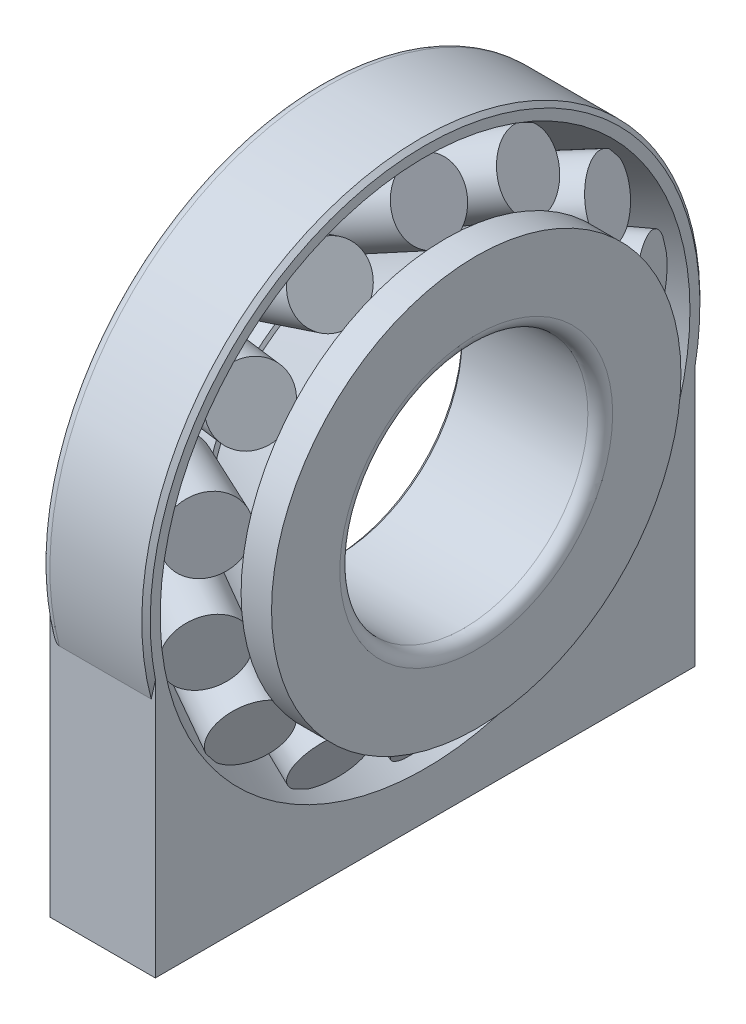
SolidWorks part; units mm, degrees
revolve "OuterRace" add sketch "OutRacSke" angle 360 about L5
sketch "OutRacSke" plane through (0, 0, 0) normal (0, 0, 1) x (1, 0, 0)
  line L0 (-8.25, 42.7146) -> (-25.25, 33.492)
  line L1 (-25.25, 33.492) -> (-25.25, 43.5)
  line L2 (-23.75, 45) -> (-8.93, 45)
  line L3 (-8.93, 45) -> (-8.25, 44.32)
  line L4 (-8.25, 44.32) -> (-8.25, 42.7146)
  line L5 (-42.5, 0) -> (42.5, 0) construction
  arc A0 (-25.25, 43.5) -> (-23.75, 45) centre (-23.75, 43.5) cw
  dimension "cup_radius" = 1.5
  dimension "OD" = 90
  dimension "cup_width" = 17
  dimension "Tangle" = 28.48
  dimension "offset" = 25.25
  dimension "chamfer" = 0.68
  dimension "D8" = 45
  dimension "cup_SID" = 66.984
ref_plane "Plane1" through (0, 0, 0) normal (0, 0, 1) x (1, 0, 0)
ref_plane "Plane2" through (0, 0, 0) normal (0, 1, 0) x (1, 0, 0)
ref_plane "Plane3" through (0, 0, 0) normal (1, 0, 0) x (0, 0, -1)
sketch "Clipboard" plane through (0, 0, 0) normal (0, 0, 1) x (1, 0, 0)
  line L0 (0, 0) -> (10, 0) construction
  line L1 (0, 0) -> (64.9943, -16.2049)
  line L2 (0, 0) -> (38.8118, 9.6769)
  line L3 (0, 0) -> (87.3266, -21.773)
  line L4 (0, 0) -> (-15.2977, -0.267)
  line L5 (0, 0) -> (-11.25, 25.25)
  dimension "Bore" = 40
  dimension "Count" = 14
  dimension "Show_count" = 14
  dimension "Max_count" = 14
  dimension "Min_count" = 1
  dimension "Race_OD" = 90
  dimension "Race_ID" = 66.984
  dimension "cyl_len" = 15.3
  dimension "Roller_diameter" = 11.25
  dimension "OA_width" = 25.25
sketch "RolDetSke" plane through (0, 0, 0) normal (0, 0, 1) x (1, 0, 0)
  line L0 (-21.0677, 29.533) -> (-23.75, 34.4773)
  line L1 (-21.0677, 29.533) -> (-7.6193, 36.8288)
  line L2 (-10.3016, 41.7731) -> (-7.6193, 36.8288)
  line L4 (-33.4195, 22.8321) -> (13.1575, 48.1003) construction
  line L5 (-10.3016, 41.7731) -> (-23.75, 34.4773)
  line L9 (-8.25, 42.7146) -> (-25.25, 33.492) construction
  dimension "cyl_len" = 15.3
  dimension "Roller_diameter" = 11.25
  dimension "dy" = 34.4773
  dimension "D2" = 23.75
revolve "RollerDetailed" add sketch "RolDetSke" angle 360 about L4
sketch "RolSimSke" plane through (0, 0, 0) normal (0, 0, 1) x (1, 0, 0)
  line L0 (0, 0) -> (-32, 0) construction
  line L1 (-23.75, 34.4773) -> (-10.3016, 41.7731)
  line L2 (-23.75, 34.4773) -> (-18.3854, 24.5887)
  line L3 (-18.3854, 24.5887) -> (-4.937, 31.8846)
  line L4 (-10.3016, 41.7731) -> (-4.937, 31.8846)
  dimension "Tangle" = 28.48
  dimension "Roller_diameter" = 11.25
  dimension "dy" = 34.4773
  dimension "dx" = 23.75
revolve "RollersSimplified" [suppressed] add sketch "RolSimSke" angle 360 about L0
ref_axis "Axis1" through (-50, 0, 0) along (1, 0, 0)
pattern_circular "RollersDetailed" count 14 every 25.714 about axis through (-50, 0, 0) along (1, 0, 0) of "RollerDetailed", "OuterRace"
sketch "InsRacSke" plane through (0, 0, 0) normal (0, 0, 1) x (1, 0, 0)
  line L0 (-18.6638, 25.1512) -> (-23, 25.1512)
  line L1 (-25.25, 43.5) -> (-25.25, -43.5) construction
  line L2 (-23, 25.1512) -> (-23, 20.68)
  line L3 (-23, 20.68) -> (-22.32, 20)
  line L4 (-22.32, 20) -> (-2, 20)
  line L5 (0, 22) -> (0, 33.0096)
  line L6 (0, 33.0096) -> (-4.9101, 33.0096)
  line L7 (-4.9101, 33.0096) -> (-4.9101, 31.8846)
  line L8 (-4.9101, 31.8846) -> (-18.3586, 24.5887)
  line L9 (-18.3586, 24.5887) -> (-18.6638, 25.1512)
  line L10 (-42.5, 0) -> (42.5, 0) construction
  arc A0 (-2, 20) -> (0, 22) centre (-2, 22) ccw
  dimension "Tangle" = 28.48
  dimension "chamfer" = 0.68
  dimension "Bore" = 40
  dimension "cyl_len" = 15.3
  dimension "dy" = 24.5887
  dimension "dx" = 18.3586
  dimension "D11" = 45
  dimension "D2" = 25.25
revolve "InnerRace" add sketch "InsRacSke" angle 360 about L10
sketch "CagSpiSke" plane through (0, 0, 0) normal (0, 0, 1) x (1, 0, 0)
  line L3 (-6.9468, 37.0221) -> (-21.0677, 29.3615)
  line L4 (-21.3693, 28.3446) -> (-20.654, 27.0261)
  line L6 (-42.5, 0) -> (42.5, 0) construction
  arc A1 (-21.0677, 29.3615) -> (-21.3693, 28.3446) centre (-20.7101, 28.7022) ccw
  dimension "Tangle" = 28.48
  dimension "radius" = 0.75
  dimension "dx" = 21.0677
  dimension "dy" = 29.3615
  dimension "offset" = 2.25
revolve "CageSpine" [suppressed] add sketch "CagSpiSke" angle 0.001 about L6
sketch "Esquisse2" plane through (-25.25, 0, 0) normal (-1, 0, 0) x (0, 0, 1)
  line L0 (-43.5, 0) -> (-43.5, -50.1949)
  line L1 (-43.5, -50.1949) -> (43.5, -50.1949)
  line L2 (43.5, -50.1949) -> (43.4753, -1.4655)
  circle A0 centre (0, 0) radius 43.5 construction
  arc A1 (-43.5, 0) -> (43.4753, -1.4655) centre (0, 0) ccw
extrude "Boss.-Extru.1" add sketch "Esquisse2" against normal blind 17
equation "\"OD@OutRacSke\" = \"Race_OD@Clipboard\""
equation "\"cup_SID@OutRacSke\" = \"Race_ID@Clipboard\""
equation "\"chamfer@OutRacSke\" = \"cup_width@OutRacSke\" / 25"
equation "\"offset@OutRacSke\" = \"OA_width@Clipboard\""
equation "\"D2@RolDetSke\" = \"offset@OutRacSke\" - \"cup_radius@OutRacSke\""
equation "\"dy@RolDetSke\" =  ( ( \"Race_ID@Clipboard\" / 2 ) + ( \"cup_radius@OutRacSke\" ) * tan(\"Tangle@OutRacSke\" * 3.141592654/180) ) * 1.005"
equation "\"cyl_len@RolDetSke\" = \"cyl_len@Clipboard\""
equation "\"Roller_diameter@RolDetSke\" = \"Roller_diameter@Clipboard\""
equation "\"dx@RolSimSke\" = \"offset@OutRacSke\" - \"cup_radius@OutRacSke\""
equation "\"dy@RolSimSke\" =  ( ( \"Race_ID@Clipboard\" / 2 ) + ( \"cup_radius@OutRacSke\" ) * tan(\"Tangle@OutRacSke\" * 3.141592654/180) ) * 1.005"
equation "\"Cyl_Len@RolSimSke\" = \"cyl_len@Clipboard\""
equation "\"Roller_diameter@RolSimSke\" = \"Roller_diameter@Clipboard\""
equation "\"Bore@InsRacSke\" = \"Bore@Clipboard\""
equation "\"Tangle@InsRacSke\" = \"Tangle@OutRacSke\""
equation "\"cyl_len@InsRacSke\" = \"cyl_len@Clipboard\""
equation "\"chamfer@InsRacSke\" = \"chamfer@OutRacSke\""
equation "\"D2@InsRacSke\" = \"OA_width@Clipboard\""
equation "\"dx@InsRacSke\" = \"offset@OutRacSke\" - \"cup_radius@OutRacSke\" -  (  \"Roller_diameter@Clipboard\" * 1.005 )  * sin(\"Tangle@InsRacSke\" * 3.141592654/180)"
equation "\"dy@InsRacSke\" = ( ( \"Race_ID@Clipboard\" / 2 ) + ( \"cup_radius@OutRacSke\" ) * tan(\"Tangle@OutRacSke\" * 3.141592654/180) ) * 1.005 -  ( \"Roller_diameter@Clipboard\" )  * cos(\"Tangle@InsRacSke\" * 3.141592654/180) "
equation "\"front_groove@InsRacSke\" = \"Groove_dp@InsRacSke\" / 2"
equation "\"Tangle@CagSpiSke\" = \"Tangle@OutRacSke\""
equation "\"dx@CagSpiSke\" = ( \"offset@OutRacSke\" - \"cup_radius@OutRacSke\" ) -  (  \"Roller_diameter@Clipboard\" / 2  )  * sin(\"Tangle@InsRacSke\" * 3.141592654/180)"
equation "\"dy@CagSpiSke\" = ( ( \"Race_ID@Clipboard\" / 2 ) + ( \"cup_radius@OutRacSke\" ) * tan(\"Tangle@OutRacSke\" * 3.141592654/180) )  -  ( \"Roller_diameter@Clipboard\" / 2 )  * cos(\"Tangle@InsRacSke\" * 3.141592654/180) "
equation "\"length@CagSpiSke\" = \"cyl_len@Clipboard\" * 1.05"
equation "\"offset@CagSpiSke\" = \"Roller_diameter@Clipboard\" / 5"
equation "\"radius@CagSpiSke\" = \"offset@CagSpiSke\" / 3"
equation "\"D3@CageSpine\" = \"Roller_diameter@Clipboard\" / 6"
equation "\"Max_count@Clipboard\" = int( 3.14159265 / atn(( \"Roller_diameter@Clipboard\" / 2) / sqr( \"dy@CagSpiSke\"  *  \"dy@CagSpiSke\" - ( \"Roller_diameter@Clipboard\" / 2) *  ( \"Roller_diameter@Clipboard\" / 2))))"
equation "\"Max_count@Clipboard\" = ((sgn( \"Max_count@Clipboard\" - \"Count@Clipboard\" )-1)*( \"Max_count@Clipboard\" - \"Count@Clipboard\" ))/-2+ \"Count@Clipboard\""
equation "\"Count@RollersDetailed\" = int( \"Show_count@Clipboard\" ) "
equation "\"Count@RollersDetailed\" = ((sgn( \"Count@RollersDetailed\" - \"Max_count@Clipboard\" )-1)*( \"Count@RollersDetailed\" - \"Max_count@Clipboard\" ))/-2+ \"Max_count@Clipboard\""
equation "\"Count@RollersDetailed\" = ((sgn( \"Count@RollersDetailed\" - \"Min_count@Clipboard\" )+1)*( \"Count@RollersDetailed\" - \"Min_count@Clipboard\"))/2 +\"Min_count@Clipboard\""
equation "\"Angle@RollersDetailed\" = 360.0 / \"Max_count@Clipboard\""
equation "\"Angle@CageSpine\" =  \"Angle@RollersDetailed\" * ( \"Count@RollersDetailed\" -1 + int( \"Count@RollersDetailed\" / \"Max_count@Clipboard\" ) )  + 0.001 -  int( \"Count@RollersDetailed\" / \"Max_count@Clipboard\" ) * 0.001"
equation "\"Angle@CageSpine\" =  \"Angle@CageSpine\" * int( \"Min_count@Clipboard\" / 2) + int(1 / \"Min_count@Clipboard\")  * 0.001"
equation "\"Tangle@RolSimSke\" = \"Tangle@OutRacSke\""
